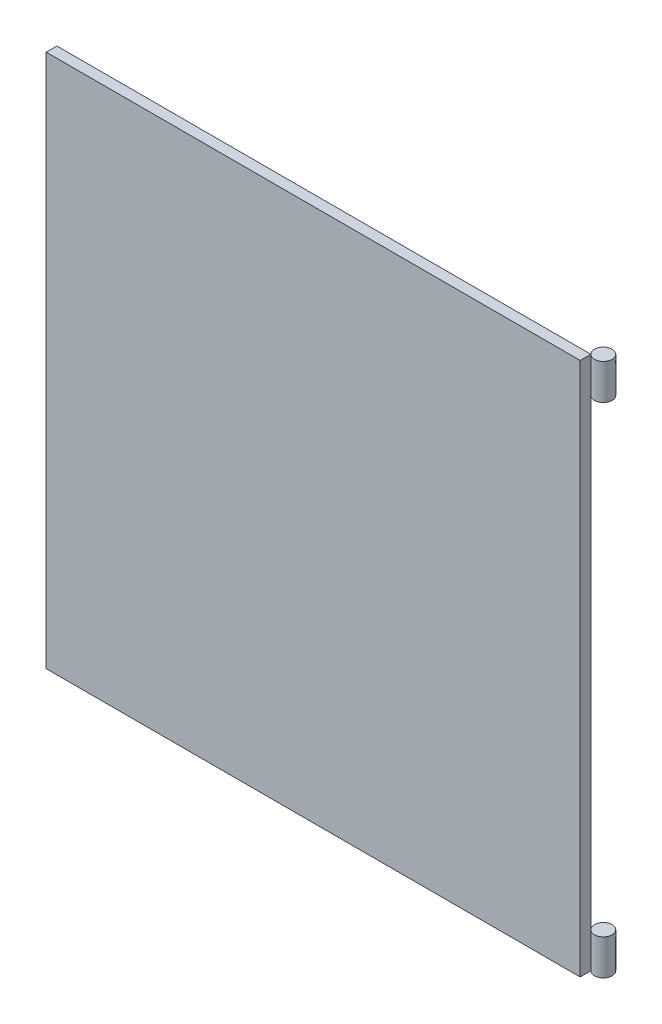
SolidWorks part; units mm, degrees
ref_plane "Alzado" through (0, 0, 0) normal (0, 0, 1) x (1, 0, 0)
ref_plane "Planta" through (0, 0, 0) normal (0, 1, 0) x (1, 0, 0)
ref_plane "Vista lateral" through (0, 0, 0) normal (1, 0, 0) x (0, 0, -1)
sketch "Croquis1" plane through (0, 0, 0) normal (0, 0, 1) x (1, 0, 0)
  line L1 (0, 0) -> (300, 0)
  line L2 (0, 0) -> (0, -300)
  line L3 (0, -300) -> (300, -300)
  line L4 (300, 0) -> (300, -300)
  dimension "D1" = 300
  dimension "D2" = 300
extrude "Saliente-Extruir1" add sketch "Croquis1" along normal blind 6
sketch "Croquis2" plane through (0, 0, 0) normal (0, 1, 0) x (1, 0, 0)
  line L0 (300, 0) -> (303.5, 0) construction
  line L1 (303.5, 0) -> (303.5, 3.5) construction
  circle A0 centre (303.5, 3.5) radius 4.9497
  dimension "D1" = 3.5
  dimension "D2" = 3.5
extrude "Saliente-Extruir2" add sketch "Croquis2" against normal blind 20 separate body
sketch "Croquis3" plane through (0, -300, 0) normal (0, -1, 0) x (1, 0, 0)
  circle A0 centre (303.5, -3.5) radius 4.9497
extrude "Saliente-Extruir3" add sketch "Croquis3" against normal blind 20 separate body
